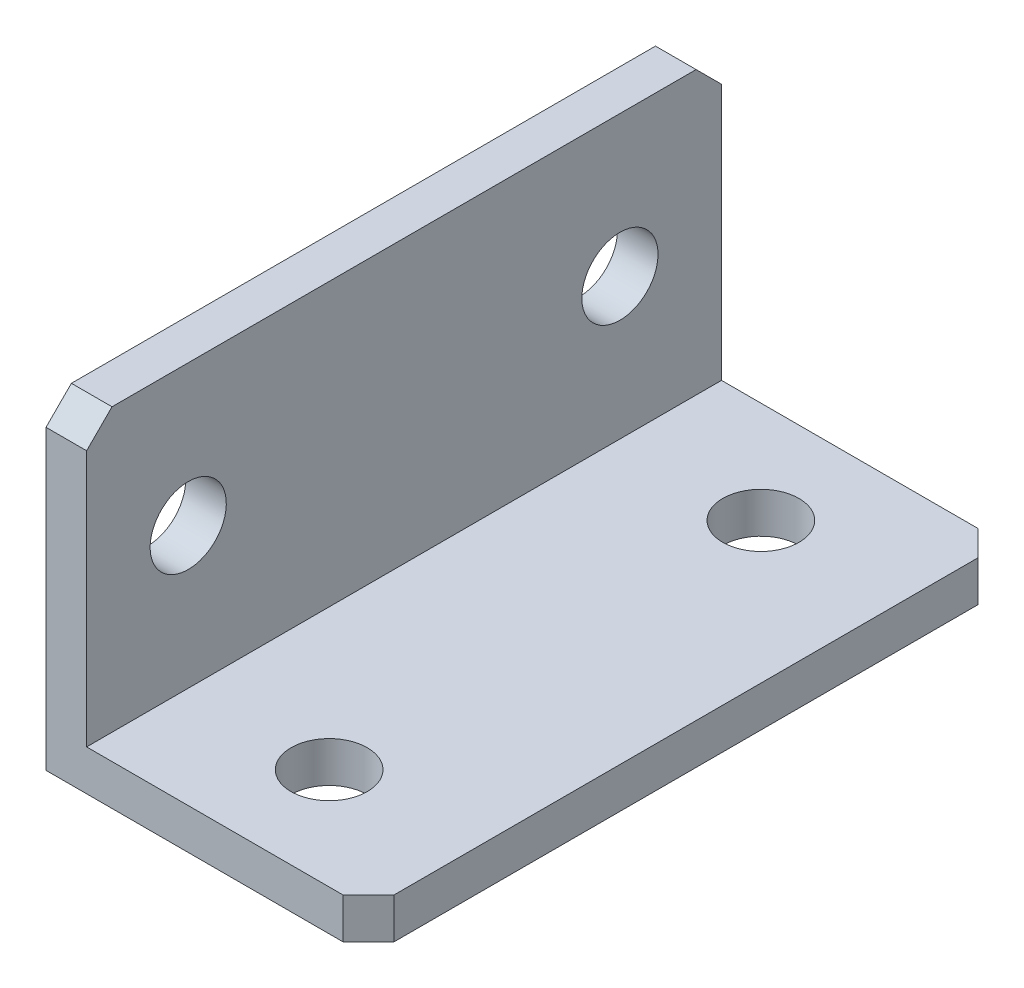
SolidWorks part; units mm, degrees
ref_plane "Plano frontal" through (0, 0, 0) normal (0, 0, 1) x (1, 0, 0)
ref_plane "Plano superior" through (0, 0, 0) normal (0, 1, 0) x (1, 0, 0)
ref_plane "Plano direito" through (0, 0, 0) normal (1, 0, 0) x (0, 0, -1)
sketch "Esboço1" plane through (0, 0, 0) normal (0, 0, 1) x (1, 0, 0)
  line L0 (0, 0) -> (0, 22.2)
  line L1 (0, 22.2) -> (-3.2, 22.2)
  line L2 (-3.2, 22.2) -> (-3.2, -3.2)
  line L3 (-3.2, -3.2) -> (22.2, -3.2)
  line L4 (22.2, -3.2) -> (22.2, 0)
  line L5 (22.2, 0) -> (0, 0)
  dimension "D1" = 3.2
  dimension "D2" = 3.2
  dimension "D3" = 25.4
  dimension "D4" = 25.4
extrude "Ressalto-extrusão1" add sketch "Esboço1" along normal blind 50
chamfer "Chanfro1" distance 2 angle 45 4 edges at (-1.6, 22.2, 0) (-1.6, 22.2, 50) (22.2, -1.6, 0) (22.2, -1.6, 50)
sketch "Esboço2" plane through (0, 0, 0) normal (0, 1, 0) x (1, 0, 0)
  line L0 (11.1, 0) -> (11.1, -50) construction
  line L1 (20.2, 0) -> (0, 0) construction
  line L2 (20.2, -50) -> (0, -50) construction
  line L3 (11.1, -25) -> (22.2, -25) construction
  line L4 (22.2, -48) -> (22.2, -2) construction
  line L5 (11.1, -25) -> (0, -25) construction
  line L6 (0, -50) -> (0, 0) construction
  circle A0 centre (11.1, -8) radius 3
  circle A1 centre (11.1, -42) radius 3
  dimension "D1" = 6
  dimension "D2" = 34
  dimension "D3" = 17
extrude "Corte-extrusão1" cut sketch "Esboço2" against normal through all
sketch "Esboço3" plane through (0, 0, 0) normal (1, 0, 0) x (0, 0, -1)
  line L0 (-50, 11.1) -> (0, 11.1) construction
  line L1 (-50, 0) -> (-50, 20.2) construction
  line L2 (0, 0) -> (0, 20.2) construction
  line L3 (-25, 11.1) -> (-25, 22.2) construction
  line L4 (-48, 22.2) -> (-2, 22.2) construction
  line L5 (-25, 0) -> (-25, 11.1) construction
  line L6 (-50, 0) -> (0, 0) construction
  circle A0 centre (-42, 11.1) radius 3
  circle A1 centre (-8, 11.1) radius 3
  dimension "D1" = 6
  dimension "D2" = 34
  dimension "D3" = 17
extrude "Corte-extrusão2" cut sketch "Esboço3" against normal through all
